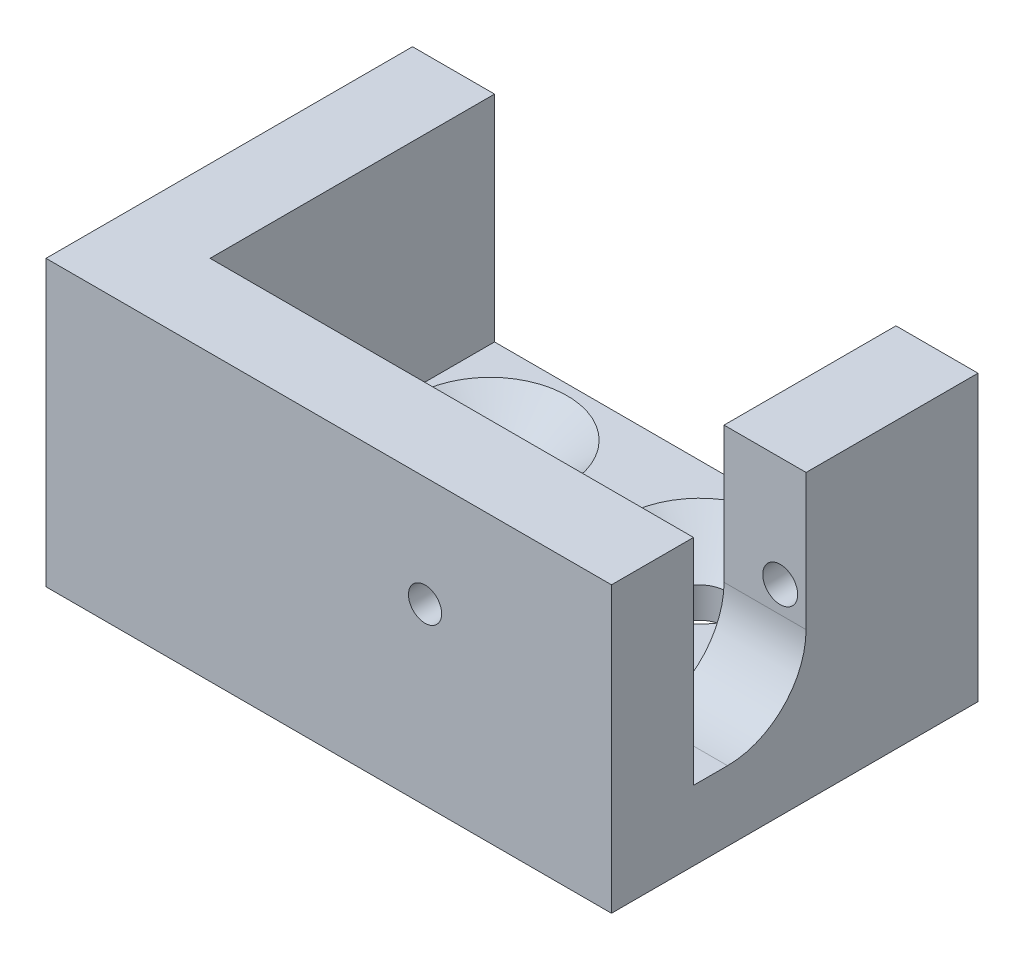
SolidWorks part; units mm, degrees
ref_plane "Plan de face" through (0, 0, 0) normal (0, 0, 1) x (1, 0, 0)
ref_plane "Plan de dessus" through (0, 0, 0) normal (0, 1, 0) x (1, 0, 0)
ref_plane "Plan de droite" through (0, 0, 0) normal (1, 0, 0) x (0, 0, -1)
sketch "Esquisse1" plane through (0, 0, 0) normal (0, 1, 0) x (1, 0, 0)
  line L0 (16.95, 0) -> (16.95, 2.4) construction
  line L1 (-15.45, 0) -> (16.95, 0)
  line L2 (-15.45, 0) -> (-15.45, -21)
  line L3 (-15.45, -21) -> (16.95, -21)
  line L4 (16.95, 0) -> (16.95, -21)
  line L5 (-15.45, 0) -> (-15.45, 2.4) construction
  line L6 (-10.75, 0) -> (-15.45, 0) construction
  dimension "D2" = 21
extrude "Boss.-Extru.1" add sketch "Esquisse1" along normal blind 4
sketch "Esquisse2" plane through (0, 4, 0) normal (0, 1, 0) x (1, 0, 0)
  line L0 (-15.45, 0) -> (-15.45, -21) construction
  line L1 (-15.45, 0) -> (-10.75, 0)
  line L2 (-15.45, 0) -> (-15.45, -21)
  line L4 (-10.75, 0) -> (-10.75, -16.3)
  line L5 (-15.45, -21) -> (16.95, -21) construction
  line L6 (16.95, -21) -> (16.95, 0) construction
  line L7 (16.95, 0) -> (12.25, 0)
  line L8 (16.95, 0) -> (16.95, -9.85)
  line L9 (16.95, -9.85) -> (12.25, -9.85)
  line L10 (12.25, 0) -> (12.25, -9.85)
  line L11 (16.95, 0) -> (-15.45, 0) construction
  line L12 (16.95, -16.3) -> (-10.75, -16.3)
  line L13 (16.95, -16.3) -> (16.95, -21)
  line L14 (16.95, -21) -> (-15.45, -21)
  line L16 (-10.75, 2.4) -> (-10.75, 6.8) construction
  line L17 (-10.75, -16.2) -> (12.25, -16.2) construction
  point P15 (0, 0)
  dimension "D1" = 0.1
  dimension "D3" = 9.85
extrude "Boss.-Extru.2" add sketch "Esquisse2" along normal blind 12.3
sketch "Esquisse3" plane through (0, 0, 21) normal (0, 0, 1) x (1, 0, 0)
  line L0 (16.95, 16.3) -> (16.95, 0) construction
  line L1 (16.95, 16.3) -> (16.95, 0) construction
  circle A0 centre (6.2684, 10) radius 0.95
  point P4 (0, 0)
  point P5 (16.95, 8.15)
  point P6 (0, 0)
  point P7 (6.115, 8.8263)
  point P8 (6.2684, 8.9642)
  point P9 (6.2684, 8.9642)
  point P10 (0, 0)
  dimension "D2" = 1.9
  dimension "D1" = 10.6816
extrude "Enlèv. mat.-Extru.1" cut sketch "Esquisse3" against normal up to next
chamfer "Chanfrein1" distance 1.915 distance2 1.6 1 edges at (7.2184, 10, 16.3)
sketch "Esquisse4" plane through (0, 0, 0) normal (0, 0, -1) x (-1, 0, 0)
  circle A0 centre (-15.4683, 10) radius 1
  circle A1 centre (13.2784, 10) radius 1
  dimension "D1" = 2
  dimension "D2" = 2
extrude "Enlèv. mat.-Extru.2" cut sketch "Esquisse4" against normal blind 10
fillet "Congé1" radius 4.5 1 edges at (14.6, 4, 9.85)
sketch "Esquisse5" plane through (0, 4, 0) normal (0, 1, 0) x (1, 0, 0)
  line L0 (12.25, 0) -> (-10.75, 0) construction
  circle A0 centre (-6, -5) radius 1.5
  circle A1 centre (6, -5) radius 1.5
  point P7 (7.4979, -3.7518)
  dimension "D1" = 3
  dimension "D2" = 12
  dimension "D3" = 6
  dimension "D4" = 5
extrude "Enlèv. mat.-Extru.3" cut sketch "Esquisse5" against normal through all
chamfer "Chanfrein2" distance 2.915 distance2 2.24 2 edges at (6, 4, 6.5) (-6, 4, 6.5)
